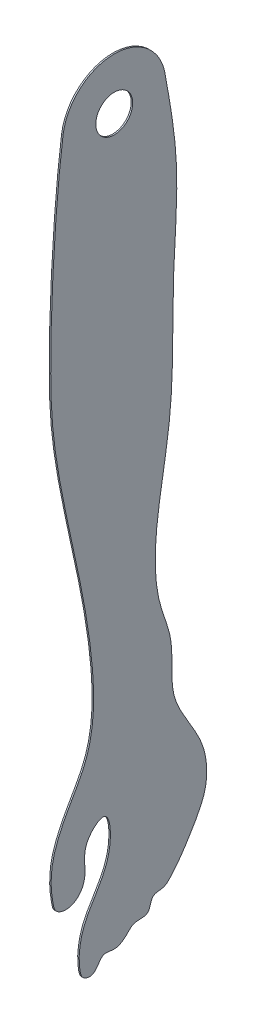
SolidWorks part; units mm, degrees
material "Teras S325"
ref_plane "Front Plane" through (0, 0, 0) normal (0, 0, 1) x (1, 0, 0)
ref_plane "Top Plane" through (0, 0, 0) normal (0, 1, 0) x (1, 0, 0)
ref_plane "Right Plane" through (0, 0, 0) normal (1, 0, 0) x (0, 0, -1)
sketch "Sketch3" plane through (0, 0, 0) normal (1, 0, 0) x (0, 0, -1)
  line L0 (0, 0) -> (0, -245.7063) construction
  circle A0 centre (0, 0) radius 12.5
  arc A1 (34.7687, 4.0168) -> (-34.6633, 4.8434) centre (0, 0) ccw
  spline S0 degree 3 poles (-34.6633, 4.8434) (-39.2097, -27.6945) (-43.8253, -94.6023) (-41.9482, -198.5983) (-14.256, -277.3228) (-12.6392, -368.6782) (-34.7779, -395.4893) (-43.9962, -424.3637) (-42.4434, -438.4929) (-40.0542, -449.3935) (-28.6472, -452.845) (-15.8627, -438.4874) (-24.6172, -420.9694) (-4.1089, -402.8256) (0.4323, -441.3014) (-22.1796, -457.5536) (-24.635, -486.5581) (-21.749, -497.1493) (-12.2917, -500.0572) (-9.3769, -487.5222) (1.2119, -491.5944) (7.8966, -486.8572) (13.4268, -480.1015) (24.4663, -483.0376) (24.5979, -470.0492) (33.1257, -471.6664) (42.7563, -462.9419) (57.4219, -439.7959) (63.5966, -421.9221) (62.0936, -393.7289) (34.9064, -366.1803) (41.4701, -330.246) (19.3598, -279.8165) (42.2093, -206.3104) (38.1854, -121.8597) (44.9238, -53.382) (38.0783, -13.9917) (34.7687, 4.0168) knots 0 0 0 0 0.081282 0.1009 0.196187 0.23017 0.256809 0.261911 0.279048 0.282147 0.290758 0.303691 0.325214 0.338388 0.352847 0.397122 0.418553 0.421852 0.430119 0.442912 0.45113 0.46226 0.468901 0.480316 0.490026 0.499359 0.503697 0.530099 0.536467 0.564082 0.611865 0.646903 0.670169 0.781144 0.870016 0.93788 0.995098 0.995098 0.995098 0.995098
  dimension "D1" = 25
  dimension "D2" = 70
extrude "Extrude1" add sketch "Sketch3" along normal mid plane 1
